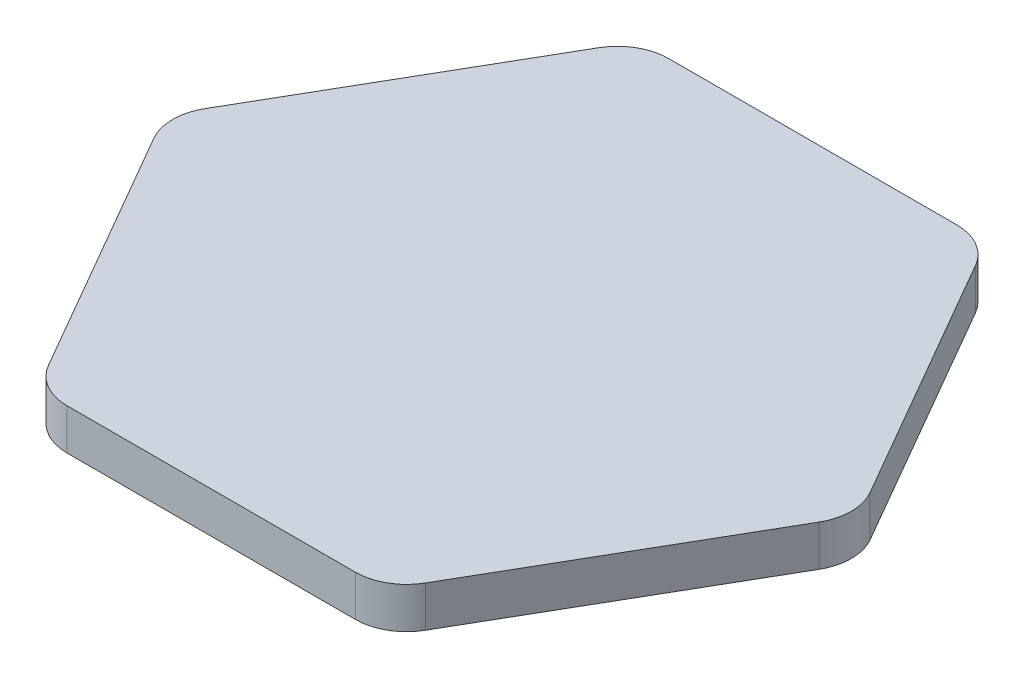
SolidWorks part; units mm, degrees
ref_plane "Front Plane" through (0, 0, 0) normal (0, 0, 1) x (1, 0, 0)
ref_plane "Top Plane" through (0, 0, 0) normal (0, 1, 0) x (1, 0, 0)
ref_plane "Right Plane" through (0, 0, 0) normal (1, 0, 0) x (0, 0, -1)
sketch "Sketch1" plane through (0, 0, 0) normal (0, 1, 0) x (1, 0, 0)
  line L6 (42.2043, 88.1) -> (-42.2043, 88.1)
  line L7 (97.399, 7.5) -> (55.1947, 80.6)
  line L8 (55.1947, -80.6) -> (97.399, -7.5)
  line L9 (-42.2043, -88.1) -> (42.2043, -88.1)
  line L10 (-97.399, -7.5) -> (-55.1947, -80.6)
  line L11 (-55.1947, 80.6) -> (-97.399, 7.5)
  arc A6 (-42.2043, 88.1) -> (-55.1947, 80.6) centre (-42.2043, 73.1) ccw
  arc A7 (55.1947, 80.6) -> (42.2043, 88.1) centre (42.2043, 73.1) ccw
  arc A8 (97.399, -7.5) -> (97.399, 7.5) centre (84.4086, 0) ccw
  arc A9 (42.2043, -88.1) -> (55.1947, -80.6) centre (42.2043, -73.1) ccw
  arc A10 (-55.1947, -80.6) -> (-42.2043, -88.1) centre (-42.2043, -73.1) ccw
  arc A11 (-97.399, 7.5) -> (-97.399, -7.5) centre (-84.4086, 0) ccw
  point P4 (-99.4086, 0)
  point P7 (0, 0)
  dimension "D2" = 15
  dimension "D1" = 84.4086
  dimension "D3" = 88.1
  dimension "D4" = 99.4086
  dimension "D5" = 42.2043
  dimension "D6" = 88.1
  dimension "D7" = 60
  dimension "D8" = 60
  dimension "D9" = 60
extrude "Boss-Extrude1" add sketch "Sketch1" against normal blind 12 separate body
sketch "Sketch2" plane through (0, 0, 0) normal (0, 1, 0) x (1, 0, 0)
